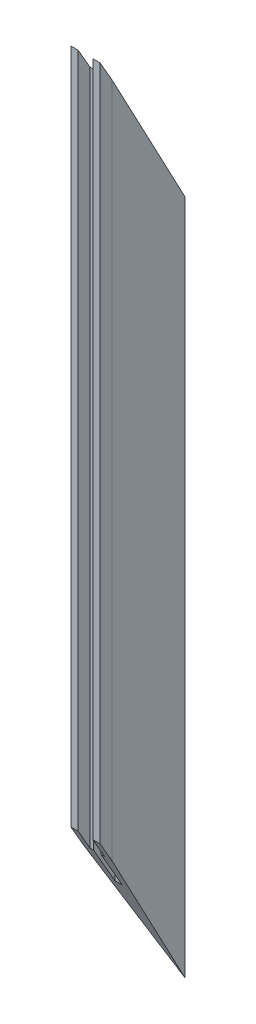
SolidWorks part; units mm, degrees
material "6061-T4 (SS)"
ref_plane "Front Plane" through (0, 0, 0) normal (0, 0, 1) x (1, 0, 0)
ref_plane "Top Plane" through (0, 0, 0) normal (0, 1, 0) x (1, 0, 0)
ref_plane "Right Plane" through (0, 0, 0) normal (1, 0, 0) x (0, 0, -1)
sketch "Sketch1" plane through (0, 0, 0) normal (0, 1, 0) x (1, 0, 0)
  line L0 (0, 0) -> (0, 38.1) construction
  line L1 (0, 38.1) -> (-6.35, 0)
  line L2 (0, 38.1) -> (6.35, 0)
  line L3 (0, 18.7872) -> (3.2182, -0.522) construction
  line L4 (0, 18.7872) -> (-3.2182, -0.522) construction
  line L5 (0, 0) -> (3.175, 0) construction
  line L6 (0, 0) -> (-3.175, 0) construction
  line L7 (-3.175, 0) -> (-3.175, -5.08)
  line L8 (-3.175, -5.08) -> (-6.35, -5.08)
  line L9 (-6.35, -5.08) -> (-6.35, 0)
  line L10 (3.175, 0) -> (3.175, -5.08)
  line L11 (3.175, -5.08) -> (6.35, -5.08)
  line L12 (6.35, -5.08) -> (6.35, 0)
  line L13 (-3.175, 0) -> (-1.5875, 0)
  line L14 (-1.5875, 0) -> (-1.5875, 9.2622)
  line L15 (-1.5875, 9.2622) -> (1.5875, 9.2622)
  line L16 (1.5875, 9.2622) -> (1.5875, 0)
  line L17 (1.5875, 0) -> (3.175, 0)
  dimension "D7" = 1.5875
  dimension "D1" = 38.1
  dimension "D2" = 6.35
  dimension "D3" = 6.35
  dimension "D5" = 3.175
  dimension "D6" = 3.175
  dimension "D8" = 5.08
  dimension "D9" = 5.08
  dimension "D4" = 3.175
extrude "Boss-Extrude1" add sketch "Sketch1" along normal blind 369.316
sketch "Sketch2" plane through (-6.35, 0, 0) normal (-1, 0, 0) x (0, 0, 1)
  line L0 (5.08, 369.316) -> (-38.1, 294.2237)
  line L1 (-38.1, 369.316) -> (-38.1, 0) construction
  line L2 (5.08, 369.316) -> (5.08, 0) construction
  line L3 (-38.1, 294.2237) -> (-38.1, 369.316)
  line L4 (-38.1, 369.316) -> (5.08, 369.316)
  dimension "D1" = 29.9
extrude "Cut-Extrude1" cut sketch "Sketch2" against normal blind 17.526
sketch "Sketch3" plane through (-6.35, 0, 0) normal (-1, 0, 0) x (0, 0, 1)
  line L0 (5.08, 76.2) -> (-38.1, 1.1077)
  line L1 (5.08, 369.316) -> (5.08, 0) construction
  line L2 (-38.1, 1.1077) -> (-38.1, 0)
  line L3 (-38.1, 0) -> (5.08, 0)
  line L4 (5.08, 0) -> (5.08, 76.2)
  dimension "D1" = 150.1
  dimension "D2" = 293.116
extrude "Cut-Extrude2" cut sketch "Sketch3" against normal blind 17.526
